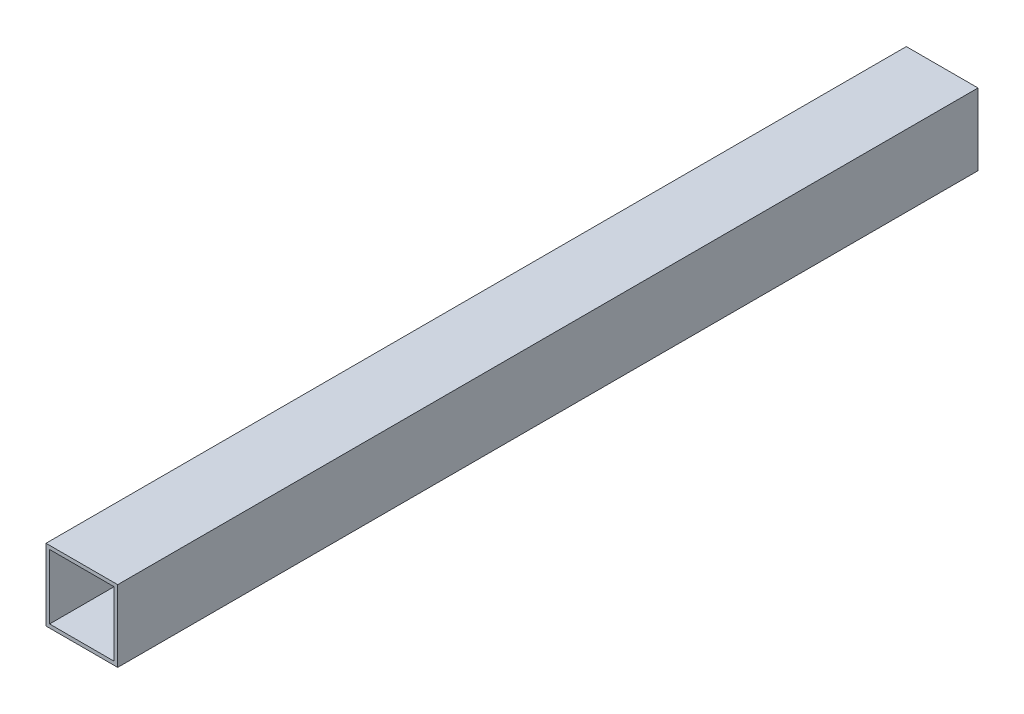
SolidWorks part; units mm, degrees
material "1.0715 (11SMn30)"
ref_plane "Alzado" through (0, 0, 0) normal (0, 0, 1) x (1, 0, 0)
ref_plane "Planta" through (0, 0, 0) normal (0, 1, 0) x (1, 0, 0)
ref_plane "Vista lateral" through (0, 0, 0) normal (1, 0, 0) x (0, 0, -1)
sketch "Croquis1" plane through (0, 0, 0) normal (0, 0, 1) x (1, 0, 0)
  line L0 (-22.5, -22.5) -> (-22.5, 22.5)
  line L1 (-25, -25) -> (25, -25)
  line L2 (-25, -25) -> (-25, 25)
  line L3 (-25, 25) -> (25, 25)
  line L4 (25, -25) -> (25, 25)
  line L5 (-25, -25) -> (25, 25) construction
  line L6 (-25, 25) -> (25, -25) construction
  line L7 (-22.5, 22.5) -> (22.5, 22.5)
  line L8 (22.5, -22.5) -> (22.5, 22.5)
  line L9 (-22.5, -22.5) -> (22.5, -22.5)
  point P0 (0, 0)
  dimension "D1" = 50
  dimension "D2" = 50
  dimension "D3" = 2.5
extrude "Saliente-Extruir1" add sketch "Croquis1" along normal mid plane 600
